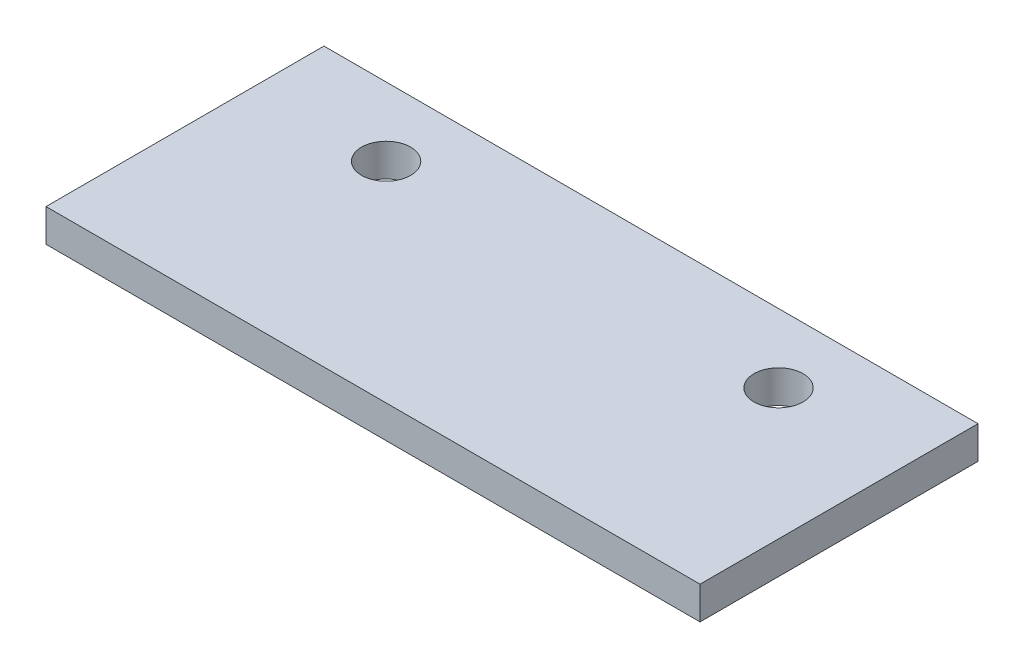
SolidWorks part; units mm, degrees
material "Plain Carbon Steel"
ref_plane "Front Plane" through (0, 0, 0) normal (0, 0, 1) x (1, 0, 0)
ref_plane "Top Plane" through (0, 0, 0) normal (0, 1, 0) x (1, 0, 0)
ref_plane "Right Plane" through (0, 0, 0) normal (1, 0, 0) x (0, 0, -1)
sketch "Sketch1" plane through (0, 0, 0) normal (0, 1, 0) x (1, 0, 0)
  line L1 (100, -42.5) -> (-100, -42.5)
  line L2 (100, -42.5) -> (100, 42.5)
  line L3 (100, 42.5) -> (-100, 42.5)
  line L4 (-100, -42.5) -> (-100, 42.5)
  line L5 (100, -42.5) -> (-100, 42.5) construction
  line L6 (100, 42.5) -> (-100, -42.5) construction
  point P0 (0, 0)
  dimension "D1" = 85
  dimension "D2" = 200
extrude "Boss-Extrude1" add sketch "Sketch1" along normal blind 10
sketch "Sketch2" plane through (0, 10, 0) normal (0, 1, 0) x (1, 0, 0)
  line L0 (100, 42.5) -> (-100, 42.5) construction
  circle A0 centre (-60, 21.5) radius 7.5
  dimension "D1" = 21
  dimension "D2" = 60
  dimension "D3" = 15
extrude "Cut-Extrude1" cut sketch "Sketch2" against normal blind 10
mirror "Mirror1" about plane through (0, 0, 0) normal (1, 0, 0) of "Cut-Extrude1"
